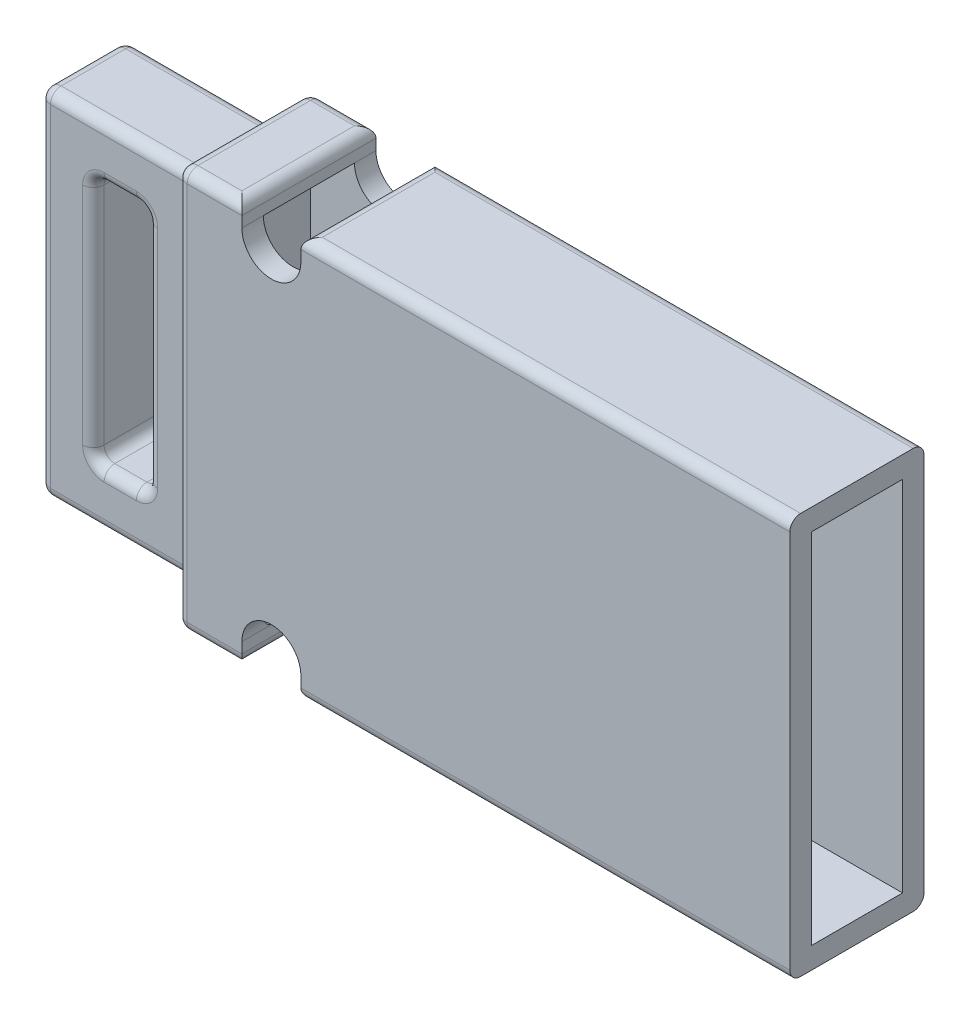
SolidWorks part; units mm, degrees
ref_plane "Front Plane" through (0, 0, 0) normal (1, 0, 0) x (0, 1, 0)
ref_plane "Top Plane" through (0, 0, 0) normal (0, 0, 1) x (0, 1, 0)
ref_plane "Right Plane" through (0, 0, 0) normal (0, 1, 0) x (-1, 0, 0)
sketch "Sketch1" plane through (0, 0, 0) normal (0, 0, 1) x (0, 1, 0)
  line L9 (0, 0) -> (-37.4, 0)
  line L12 (0, 0) -> (0, 57.2)
  line L13 (0, 57.2) -> (-37.4, 57.2)
  line L14 (-37.4, 0) -> (-37.4, 57.2)
  dimension "D1" = 57.2
  dimension "D2" = 37.4
extrude "Boss-Extrude1" add sketch "Sketch1" along normal blind 12.5
shell "Shell1" thickness 2
sketch "Sketch2" plane through (0, 0, 12.5) normal (0, 0, 1) x (1, 0, 0)
  line L0 (-51.1, -37.4) -> (-51.1, -35.4)
  line L1 (-57.2, -37.4) -> (0, -37.4) construction
  line L2 (-45.6, -37.4) -> (-45.6, -35.4)
  line L3 (-51.1, 0) -> (-51.1, -2)
  line L4 (0, 0) -> (-57.2, 0) construction
  line L5 (-45.6, 0) -> (-45.6, -2)
  line L6 (0, -37.4) -> (0, 0) construction
  line L7 (-45.6, -37.4) -> (-51.1, -37.4)
  line L8 (-51.1, 0) -> (-45.6, 0)
  arc A0 (-51.1, -35.4) -> (-45.6, -35.4) centre (-48.35, -35.4) cw
  arc A1 (-51.1, -2) -> (-45.6, -2) centre (-48.35, -2) ccw
  dimension "D1" = 2
  dimension "D2" = 45.6
  dimension "D3" = 5.5
extrude "Cut-Extrude1" cut sketch "Sketch2" against normal through all
sketch "Sketch3" plane through (-57.2, 0, 0) normal (-1, 0, 0) x (0, -1, 0)
  line L0 (0, 6.25) -> (37.4, 6.25) construction
  line L1 (0, 12.5) -> (0, 0) construction
  line L2 (37.4, 12.5) -> (37.4, 0) construction
  line L3 (18.7, 12.5) -> (18.7, 0) construction
  line L4 (0, 12.5) -> (37.4, 12.5) construction
  line L5 (0, 0) -> (37.4, 0) construction
  line L7 (2.2, 2.25) -> (35.2, 2.25)
  line L8 (2.2, 2.25) -> (2.2, 10.25)
  line L9 (2.2, 10.25) -> (35.2, 10.25)
  line L10 (35.2, 2.25) -> (35.2, 10.25)
  line L11 (2.2, 2.25) -> (35.2, 10.25) construction
  line L12 (2.2, 10.25) -> (35.2, 2.25) construction
  point P12 (18.7, 6.25)
  dimension "D1" = 8
  dimension "D2" = 33
extrude "Boss-Extrude2" add sketch "Sketch3" along normal blind 15
sketch "Sketch4" plane through (0, 0, 2.25) normal (0, 0, -1) x (1, 0, 0)
  line L8 (-62.2, 7.2) -> (-62.2, 30.2)
  line L9 (-62.2, 30.2) -> (-67.2, 30.2)
  line L10 (-67.2, 30.2) -> (-67.2, 7.2)
  line L11 (-67.2, 7.2) -> (-62.2, 7.2)
  line L12 (-62.2, 7.2) -> (-62.2, 30.2)
  line L13 (-62.2, 30.2) -> (-67.2, 30.2)
  line L14 (-67.2, 30.2) -> (-67.2, 7.2)
  line L15 (-67.2, 7.2) -> (-62.2, 7.2)
  dimension "D1" = 5
extrude "Cut-Extrude2" cut sketch "Sketch4" against normal through all
fillet "Fillet2" radius 1 41 edges at (-64.7, -7.2, 10.25) (-67.2, -18.7, 10.25) (-64.7, -30.2, 10.25) (-62.2, -18.7, 10.25) (-64.7, -30.2, 2.25) (-67.2, -18.7, 2.25) (-64.7, -7.2, 2.25) (-62.2, -18.7, 2.25) (-72.2, -18.7, 2.25) (-72.2, -18.7, 10.25) (-72.2, -2.2, 6.25) (-64.7, -2.2, 10.25) (-64.7, -2.2, 2.25) (-72.2, -35.2, 6.25) (-64.7, -35.2, 10.25) (-64.7, -35.2, 2.25) (-57.2, -18.7, 12.5) (-57.2, 0, 6.25) (-57.2, -37.4, 6.25) (-53.15, -35.4, 10.5) (-57.2, -18.7, 0) (-51.1, 0, 6.25) (-45.6, 0, 6.25) (-45.6, -37.4, 6.25) (-51.1, -37.4, 6.25) (-57.2, -35.2, 6.25) (-57.2, -18.7, 2.25) (-57.2, -18.7, 10.25) (-57.2, -2.2, 6.25) (-54.15, 0, 12.5) (-54.15, 0, 0) (-54.15, -37.4, 12.5) (-54.15, -37.4, 0) (-22.8, -37.4, 0) (-22.8, -37.4, 12.5) (-22.8, 0, 12.5) (-22.8, 0, 0) (-67.2, -30.2, 6.25) (-62.2, -30.2, 6.25) (-62.2, -7.2, 6.25) (-67.2, -7.2, 6.25)
equation "\"BoxWidth\"=12.5"
equation "\"BoxThickness\"= 37.4"
equation "\"BoxLength\" = 57.2"
equation "\"wall\"=2"
equation "\"WindowOffset\"= 45.6"
equation "\"WindowHeight\"= 2"
equation "\"WindowLength\"= 5.5"
equation "\"WindowRadius\"= 2.75"
equation "\"D1@Boss-Extrude1\"=\"BoxWidth\""
equation "\"D1@Sketch1\"=\"BoxLength\""
equation "\"D2@Sketch1\"=\"BoxThickness\""
equation "\"D1@Shell1\"=\"wall\""
equation "\"D1@Sketch2\"=\"WindowHeight\""
equation "\"D2@Sketch2\"=\"WindowOffset\""
equation "\"D3@Sketch2\"=\"WindowLength\""
